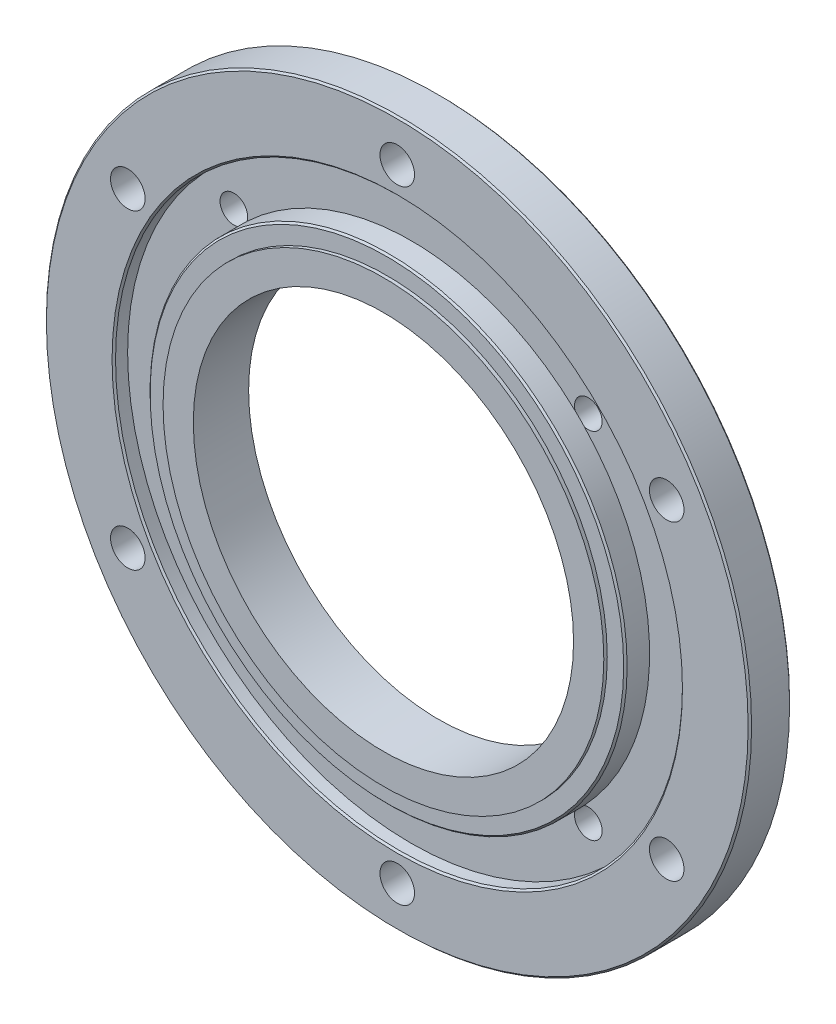
SolidWorks part; units mm, degrees
ref_plane "前视基准面" through (0, 0, 0) normal (0, 0, 1) x (1, 0, 0)
ref_plane "上视基准面" through (0, 0, 0) normal (0, 1, 0) x (1, 0, 0)
ref_plane "右视基准面" through (0, 0, 0) normal (1, 0, 0) x (0, 0, -1)
sketch "草图1" plane through (0, 0, 0) normal (0, 0, 1) x (1, 0, 0)
  circle A0 centre (0, 0) radius 102
  dimension "D1" = 204
extrude "拉伸1" add sketch "草图1" along normal blind 12
sketch "草图2" plane through (0, 0, 12) normal (0, 0, 1) x (1, 0, 0)
  circle A0 centre (0, 0) radius 69
  dimension "D1" = 138
extrude "拉伸2" add sketch "草图2" along normal blind 3
sketch "草图3" plane through (0, 0, 12) normal (0, 0, 1) x (1, 0, 0)
  circle A0 centre (0, 0) radius 69
  circle A1 centre (0, 0) radius 82
  dimension "D1" = 164
extrude "切除-拉伸2" cut sketch "草图3" against normal blind 4
sketch "草图4" plane through (0, 0, 15) normal (0, 0, 1) x (1, 0, 0)
  circle A0 centre (0, 0) radius 63.75
extrude "拉伸3" add sketch "草图4" along normal blind 1
chamfer "倒角1" distance 0.5 angle 45 4 edges at (69, 0, 15) (82, 0, 12) (102, 0, 0) (102, 0, 12)
sketch "草图5" plane through (0, 0, 0) normal (0, 0, -1) x (-1, 0, 0)
  circle A1 centre (0, 90) radius 5
  circle A2 centre (77.9423, 45) radius 5
  circle A3 centre (77.9423, -45) radius 5
  circle A4 centre (0, -90) radius 5
  circle A5 centre (-77.9423, -45) radius 5
  circle A6 centre (-77.9423, 45) radius 5
  dimension "D2" = 10
extrude "切除-拉伸3" cut sketch "草图5" against normal blind 41
sketch "草图6" plane through (0, 0, 0) normal (0, 0, -1) x (-1, 0, 0)
  circle A0 centre (0, 0) radius 55
extrude "切除-拉伸4" cut sketch "草图6" against normal blind 51
sketch "草图7" plane through (0, 0, 0) normal (0, 0, -1) x (-1, 0, 0)
  circle A1 centre (51.2652, 51.2652) radius 4
  circle A2 centre (51.2652, -51.2652) radius 4
  circle A3 centre (-51.2652, -51.2652) radius 4
  circle A4 centre (-51.2652, 51.2652) radius 4
  dimension "D2" = 8
extrude "切除-拉伸5" cut sketch "草图7" against normal blind 8
